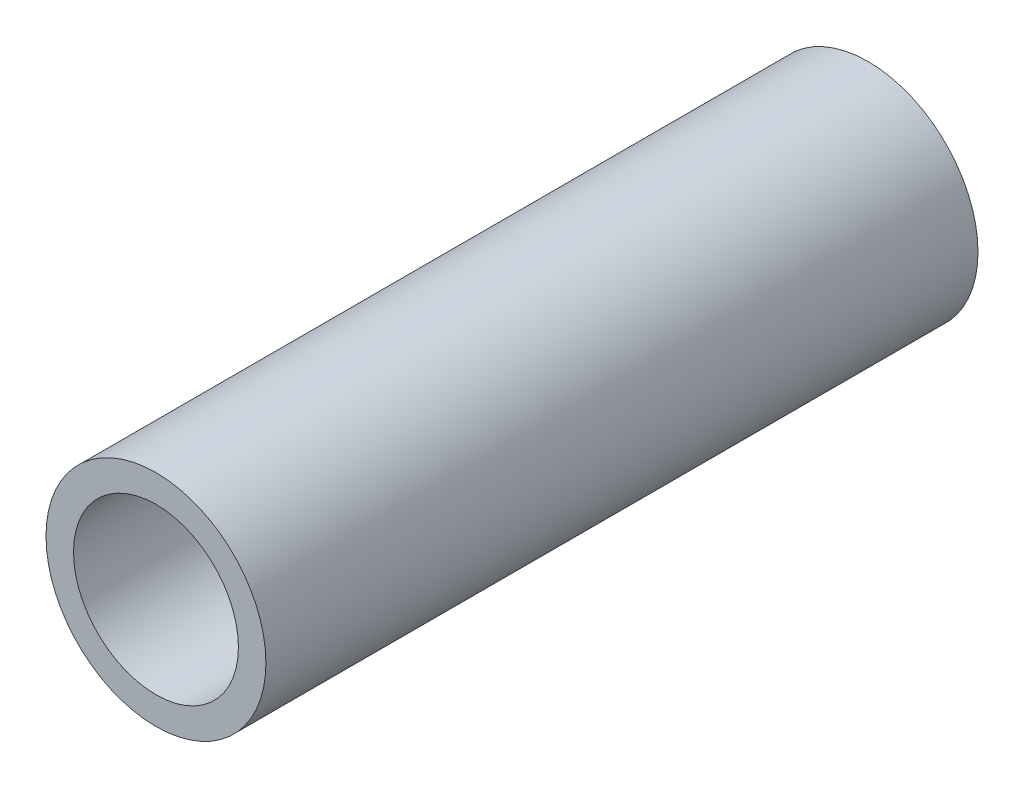
SolidWorks part; units mm, degrees
ref_plane "Front Plane" through (0, 0, 0) normal (0, 0, 1) x (1, 0, 0)
ref_plane "Top Plane" through (0, 0, 0) normal (0, 1, 0) x (1, 0, 0)
ref_plane "Right Plane" through (0, 0, 0) normal (1, 0, 0) x (0, 0, -1)
sketch "Sketch1" plane through (0, 0, 0) normal (0, 0, 1) x (1, 0, 0)
  circle A0 centre (0, 0) radius 3.15
  circle A1 centre (0, 0) radius 4.2
  dimension "D1" = 6.3
  dimension "D2" = 8.4
extrude "Boss-Extrude1" add sketch "Sketch1" along normal blind 27.2
